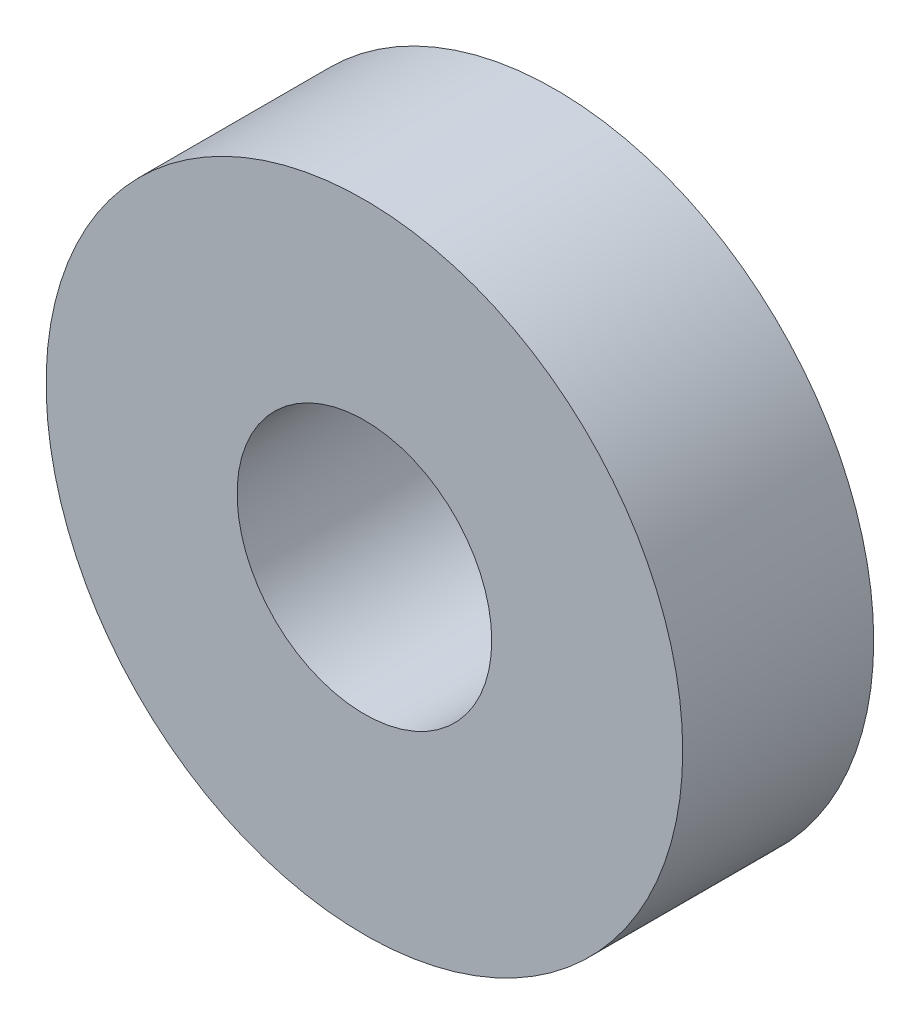
SolidWorks part; units mm, degrees
ref_plane "Front Plane" through (0, 0, 0) normal (0, 0, 1) x (1, 0, 0)
ref_plane "Top Plane" through (0, 0, 0) normal (0, 1, 0) x (1, 0, 0)
ref_plane "Right Plane" through (0, 0, 0) normal (1, 0, 0) x (0, 0, -1)
sketch "Sketch1" plane through (0, 0, 0) normal (0, 0, 1) x (1, 0, 0)
  circle A0 centre (0, 0) radius 4
  circle A1 centre (0, 0) radius 1.6
  dimension "OD" = 8
  dimension "ID1" = 3.2
extrude "Boss-Extrude1" add sketch "Sketch1" along normal blind 2.4
